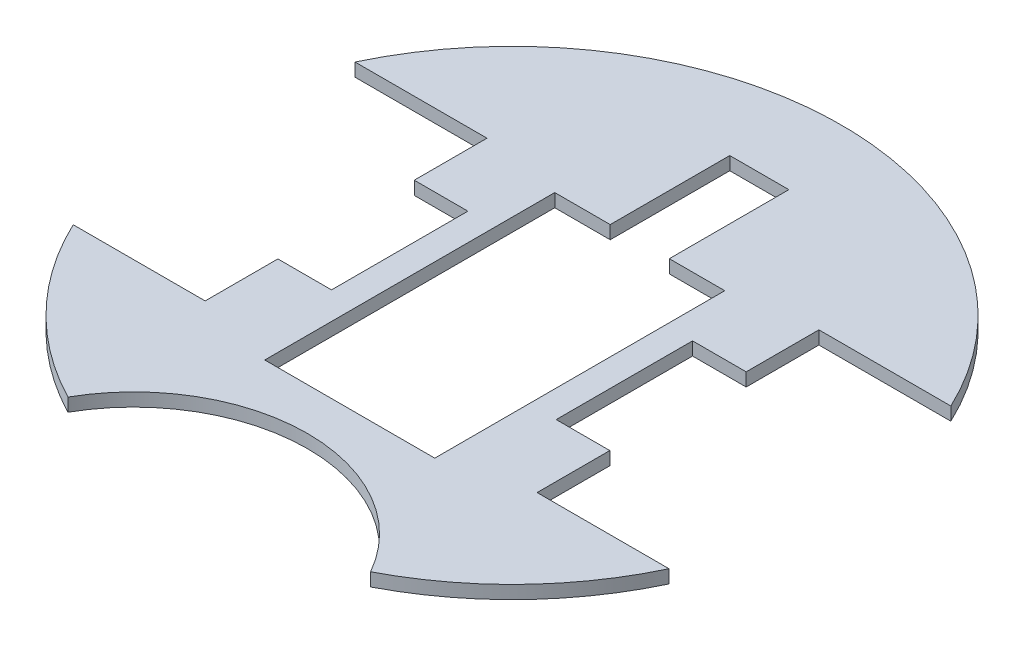
SolidWorks part; units mm, degrees
ref_plane "Front Plane" through (0, 0, 0) normal (0, 0, 1) x (1, 0, 0)
ref_plane "Top Plane" through (0, 0, 0) normal (0, 1, 0) x (1, 0, 0)
ref_plane "Right Plane" through (0, 0, 0) normal (1, 0, 0) x (0, 0, -1)
sketch "Sketch1" plane through (0, 0, 0) normal (0, 1, 0) x (1, 0, 0)
  line L0 (0, -83.2398) -> (-33.2911, -64.4046) construction
  line L1 (0, -83.2398) -> (0, 0) construction
  arc A0 (33.2911, -64.4046) -> (-33.2911, -64.4046) centre (0, 0) ccw
  arc A1 (33.2911, -64.4046) -> (-33.2911, -64.4046) centre (0, -83.2398) ccw
  dimension "D1" = 145
  dimension "D2" = 76.5
  dimension "D3" = 60.5
extrude "Boss-Extrude1" add sketch "Sketch1" along normal blind 2.9
sketch "solenoid placement" plane through (0, 2.9, 0) normal (0, 1, 0) x (1, 0, 0)
  line L4 (-18.7, -35.7) -> (18.7, -35.7)
  line L5 (18.7, -35.7) -> (18.7, 28.1)
  line L6 (18.7, 28.1) -> (-18.7, 28.1)
  line L7 (-18.7, 28.1) -> (-18.7, -35.7)
  line L8 (-18.7, -35.7) -> (18.7, -35.7)
  line L9 (18.7, -35.7) -> (18.7, 28.1)
  line L10 (18.7, 28.1) -> (-18.7, 28.1)
  line L11 (-18.7, 28.1) -> (-18.7, -35.7)
  circle A1 centre (0, 0) radius 72.5 construction
  arc A2 (33.2911, -64.4046) -> (-33.2911, -64.4046) centre (0, 0) ccw construction
  dimension "D1" = 0
extrude "Cut-Extrude1" cut sketch "solenoid placement" against normal through all
sketch "Sketch3" plane through (0, 2.9, 0) normal (0, 1, 0) x (1, 0, 0)
  line L0 (-36.51, -15) -> (-36.51, -31)
  line L1 (-24.71, 15) -> (-36.51, 15)
  line L2 (-24.71, 15) -> (-24.71, -15)
  line L3 (-24.71, -15) -> (-36.51, -15)
  line L4 (0, 0) -> (0, 72.5) construction
  line L5 (-36.51, -31) -> (-65.5382, -31)
  line L6 (-36.51, 15) -> (-36.51, 31)
  line L7 (-36.51, 31) -> (-65.5382, 31)
  line L8 (36.51, 31) -> (65.5382, 31)
  line L9 (36.51, 15) -> (36.51, 31)
  line L10 (36.51, -31) -> (65.5382, -31)
  line L11 (24.71, -15) -> (36.51, -15)
  line L12 (24.71, 15) -> (24.71, -15)
  line L13 (24.71, 15) -> (36.51, 15)
  line L14 (36.51, -15) -> (36.51, -31)
  arc A0 (33.2911, -64.4046) -> (-33.2911, -64.4046) centre (0, 0) ccw construction
  arc A1 (-65.5382, 31) -> (-65.5382, -31) centre (0, 0) ccw
  arc A2 (65.5382, 31) -> (65.5382, -31) centre (0, 0) cw
  dimension "D1" = 62
extrude "Cut-Extrude3" cut sketch "Sketch3" against normal through all
sketch "Sketch4" plane through (0, 2.9, 0) normal (0, 1, 0) x (1, 0, 0)
  line L0 (18.7, 28.1) -> (-18.7, 28.1) construction
  line L1 (-6.5, 28.1) -> (6.5, 28.1)
  line L2 (-6.5, 28.1) -> (-6.5, 54.4)
  line L3 (6.5, 54.4) -> (-6.5, 54.4) construction
  line L4 (6.5, 28.1) -> (6.5, 54.4)
  line L5 (6.5, 54.4) -> (-6.5, 54.4)
  point P6 (0, 28.1)
extrude "Cut-Extrude4" cut sketch "Sketch4" against normal through all
equation "\"smallPulleyTeeth\"= 15"
equation "\"largePulleyTeeth\"= 40"
equation "\"eighthThick\"= 2.9mm"
equation "\"sixteenthThick\"= 1.7mm"
equation "\"quarterThick\"=5.9mm"
equation "\"OD\"= 145mm"
equation "\"puckAngle\"= 60.5deg"
equation "\"D1@Sketch1\"=\"OD\""
equation "\"puckDiam\"= 76.5mm"
equation "\"D2@Sketch1\"=\"puckDiam\""
equation "\"D3@Sketch1\"=\"puckAngle\""
equation "\"D1@Boss-Extrude1\"=\"eighthThick\""
equation "\"axlePress\"= 5.9mm"
equation "\"press\"= 0.2mm"
equation "\"wheelClear\"= 0.3mm"
equation "\"10-32clear\"= 4.5mm"
equation "\"6-32clear\"= 3.3mm"
equation "\"8-32clear\"= 4.0mm"
equation "\"wheelHeight\"= 24mm"
equation "\"wheelWell\"= 62mm"
equation "\"D1@Sketch3\"=\"wheelWell\""
